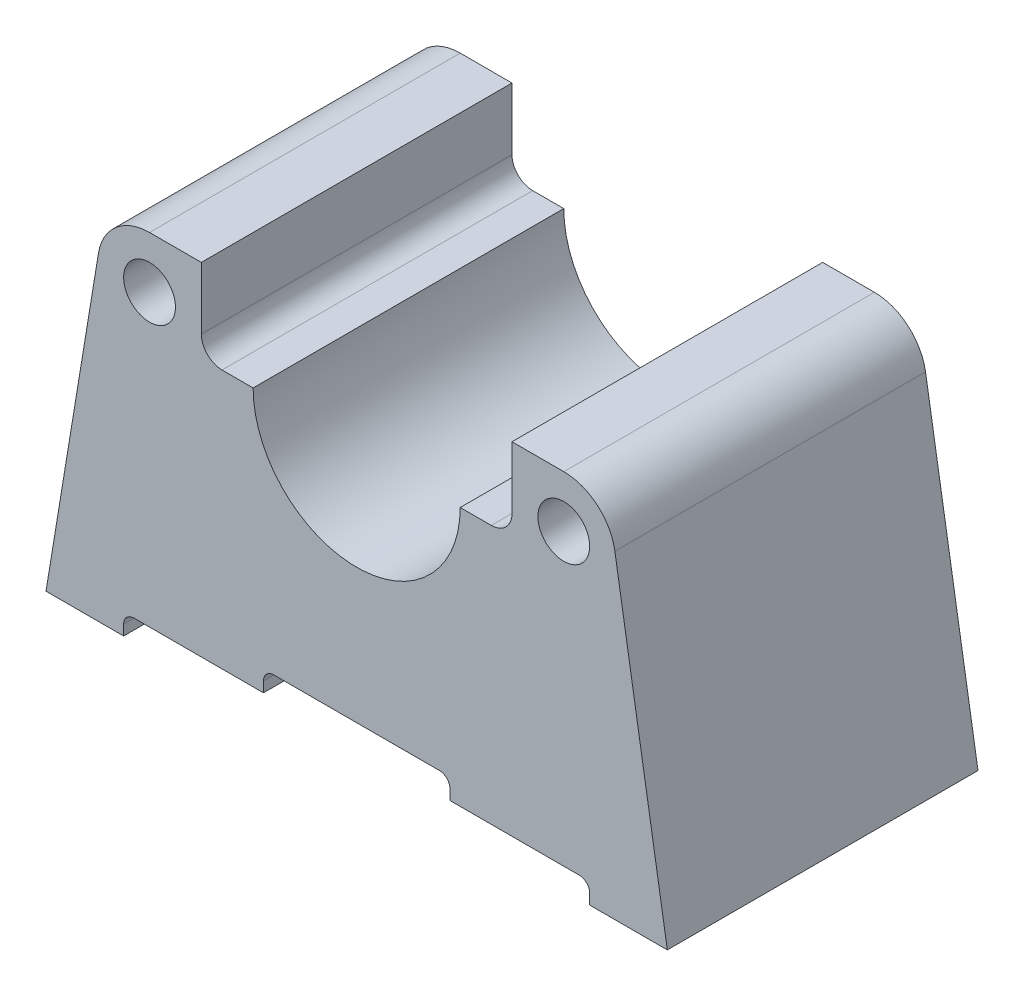
SolidWorks part; units mm, degrees
ref_plane "Front Plane" through (0, 0, 0) normal (0, 0, 1) x (1, 0, 0)
ref_plane "Top Plane" through (0, 0, 0) normal (0, 1, 0) x (1, 0, 0)
ref_plane "Right Plane" through (0, 0, 0) normal (1, 0, 0) x (0, 0, -1)
sketch "Sketch1" plane through (0, 0, 0) normal (0, 0, 1) x (1, 0, 0)
  line L0 (0, 0) -> (23106.1472, 0) construction
  line L1 (0, 0) -> (0, 23106.1472) construction
  line L2 (-8, 4) -> (8, 4)
  line L3 (9, 3) -> (9, 2)
  line L4 (9, 2) -> (21.5, 2)
  line L5 (22.5, 1) -> (22.5, 0)
  line L6 (22.5, 0) -> (30, 0)
  line L7 (30, 0) -> (24.9337, 30.8112)
  line L8 (20, 35) -> (15, 35)
  line L9 (15, 35) -> (15, 29)
  line L10 (13, 27) -> (10, 27)
  line L11 (-9, 3) -> (-9, 2)
  line L12 (-13, 27) -> (-10, 27)
  line L13 (-15, 35) -> (-15, 29)
  line L14 (-20, 35) -> (-15, 35)
  line L15 (-30, 0) -> (-24.9337, 30.8112)
  line L16 (-22.5, 0) -> (-30, 0)
  line L17 (-22.5, 1) -> (-22.5, 0)
  line L18 (-9, 2) -> (-21.5, 2)
  arc A0 (10, 27) -> (-10, 27) centre (0, 27) cw
  arc A1 (-20, 35) -> (-24.9337, 30.8112) centre (-20, 30) ccw
  arc A2 (24.9337, 30.8112) -> (20, 35) centre (20, 30) ccw
  arc A3 (15, 29) -> (13, 27) centre (13, 29) cw
  arc A4 (-13, 27) -> (-15, 29) centre (-13, 29) cw
  arc A5 (21.5, 2) -> (22.5, 1) centre (21.5, 1) cw
  arc A6 (8, 4) -> (9, 3) centre (8, 3) cw
  arc A7 (-9, 3) -> (-8, 4) centre (-8, 3) cw
  arc A8 (-22.5, 1) -> (-21.5, 2) centre (-21.5, 1) cw
  circle A9 centre (-20, 30) radius 2.5
  circle A10 centre (20, 30) radius 2.5
  point P18 (9, 2.5)
  point P19 (-9, 2.5)
  point P22 (0, 4)
  point P29 (-15, 32)
  point P32 (-24.245, 35)
  point P35 (24.245, 35)
  point P38 (15, 27)
  point P41 (-15, 27)
  point P44 (22.5, 2)
  point P47 (9, 4)
  point P50 (-9, 4)
  point P53 (-22.5, 2)
  point P56 (0, 0)
  point P57 (26.0156, 30.6447)
  point P58 (27.9773, 30)
  point P59 (0, 0)
  dimension "D6" = 5
  dimension "D7" = 2
  dimension "D8" = 1
  dimension "D11" = 10
  dimension "D15" = 5
  dimension "D1" = 18
  dimension "D2" = 45
  dimension "D3" = 60
  dimension "D4" = 2
  dimension "D5" = 4
  dimension "D9" = 35
  dimension "D10" = 27
  dimension "D12" = 40
  dimension "D13" = 30
  dimension "D14" = 30
  dimension "D16" = 40
extrude "Boss-Extrude1" add sketch "Sketch1" along normal blind 30
